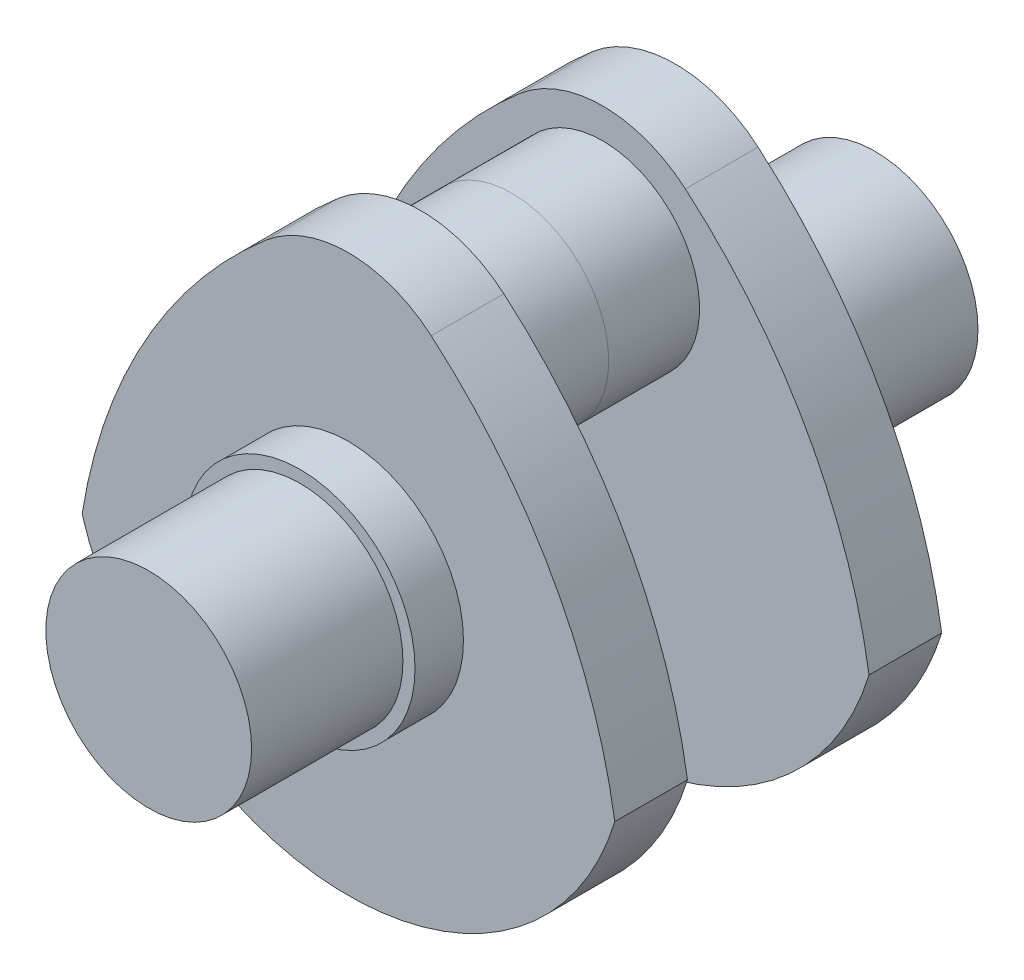
SolidWorks part; units mm, degrees
ref_plane "Front Plane" through (0, 0, 0) normal (0, 0, 1) x (1, 0, 0)
ref_plane "Top Plane" through (0, 0, 0) normal (0, 1, 0) x (1, 0, 0)
ref_plane "Right Plane" through (0, 0, 0) normal (1, 0, 0) x (0, 0, -1)
sketch "Sketch1" plane through (0, 0, 0) normal (0, 0, 1) x (1, 0, 0)
  circle A0 centre (0, 0) radius 17
  dimension "D1" = 34
extrude "Boss-Extrude1" add sketch "Sketch1" along normal blind 33
sketch "Sketch2" plane through (0, 0, 0) normal (0, 0, 1) x (1, 0, 0)
  circle A0 centre (0, 0) radius 19
  dimension "D1" = 38
extrude "Boss-Extrude2" add sketch "Sketch2" along normal blind 8
sketch "Sketch3" plane through (0, 0, 0) normal (0, 0, -1) x (-1, 0, 0)
  arc A0 (-44, -13.4164) -> (44, -13.4164) centre (0, 0) ccw
  arc A1 (13.6681, 40.9431) -> (-13.6681, 40.9431) centre (0, 25) ccw
  arc A2 (-13.6681, 40.9431) -> (-44, -13.4164) centre (44.9095, -27.3845) ccw
  arc A3 (44, -13.4164) -> (13.6681, 40.9431) centre (-44.9095, -27.3845) ccw
  dimension "D1" = 88
  dimension "D2" = 46
  dimension "D3" = 42
  dimension "D5" = 90
  dimension "D6" = 90
  dimension "D4" = 25
extrude "Boss-Extrude3" add sketch "Sketch3" along normal blind 12
sketch "Sketch4" plane through (0, 0, -12) normal (0, 0, -1) x (-1, 0, 0)
  circle A0 centre (0, 25) radius 16
  dimension "D1" = 32
  dimension "D2" = 25
extrude "Boss-Extrude4" add sketch "Sketch4" along normal blind 15
mirror "Mirror1" about plane through (0, 25, -27) normal (0, 0, -1) of bodies 104
